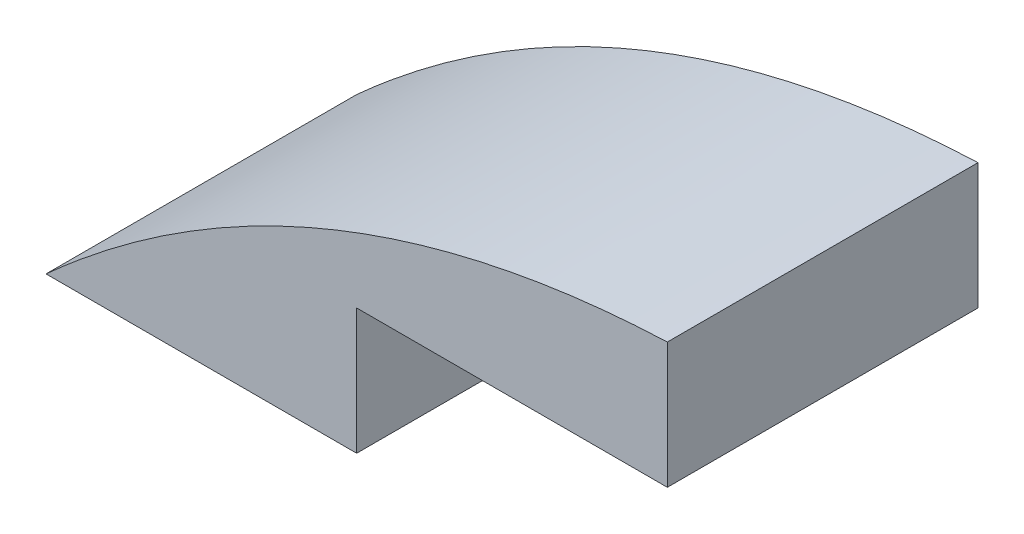
SolidWorks part; units mm, degrees
ref_plane "Front Plane" through (0, 0, 0) normal (0, 0, 1) x (1, 0, 0)
ref_plane "Top Plane" through (0, 0, 0) normal (0, 1, 0) x (1, 0, 0)
ref_plane "Right Plane" through (0, 0, 0) normal (1, 0, 0) x (0, 0, -1)
sketch "Sketch2" plane through (0, 0, 0) normal (0, 1, 0) x (1, 0, 0)
  line L1 (0, 0) -> (7.9, 0)
  line L2 (0, 0) -> (0, 7.9)
  line L3 (0, 7.9) -> (7.9, 7.9)
  line L4 (7.9, 0) -> (7.9, 7.9)
  dimension "D1" = 7.9
  dimension "D2" = 7.9
extrude "Boss-Extrude1" add sketch "Sketch2" along normal blind 3.2
sketch "Sketch3" plane through (0, 3.2, 0) normal (0, 1, 0) x (1, 0, 0)
  line L1 (7.9, 7.9) -> (15.8, 7.9)
  line L2 (7.9, 7.9) -> (7.9, 0)
  line L3 (7.9, 0) -> (15.8, 0)
  line L4 (15.8, 7.9) -> (15.8, 0)
  dimension "D1" = 7.9
extrude "Boss-Extrude2" add sketch "Sketch3" along normal blind 3.2 separate body
sketch "Sketch4" plane through (0, 0, -7.9) normal (0, 0, -1) x (-1, 0, 0)
  line L0 (-15.8, 6.4) -> (0, 6.4)
  line L1 (0, 6.4) -> (0, 0)
  spline S0 degree 2 poles (-15.8, 6.4) (-6.6846, 6.0427) (0, 0) knots 0 0 0 1 1 1
sketch "Sketch7" plane through (7.9, 0, 0) normal (-1, 0, 0) x (0, 0, 1)
  line L1 (0, 3.2) -> (-7.9, 3.2)
  line L2 (0, 3.2) -> (0, 6.4)
  line L3 (0, 6.4) -> (-7.9, 6.4)
  line L4 (-7.9, 3.2) -> (-7.9, 6.4)
extrude "Boss-Extrude5" add sketch "Sketch7" along normal blind 7.2
extrude "Cut-Extrude2" cut sketch "Sketch4" against normal blind 8.2
